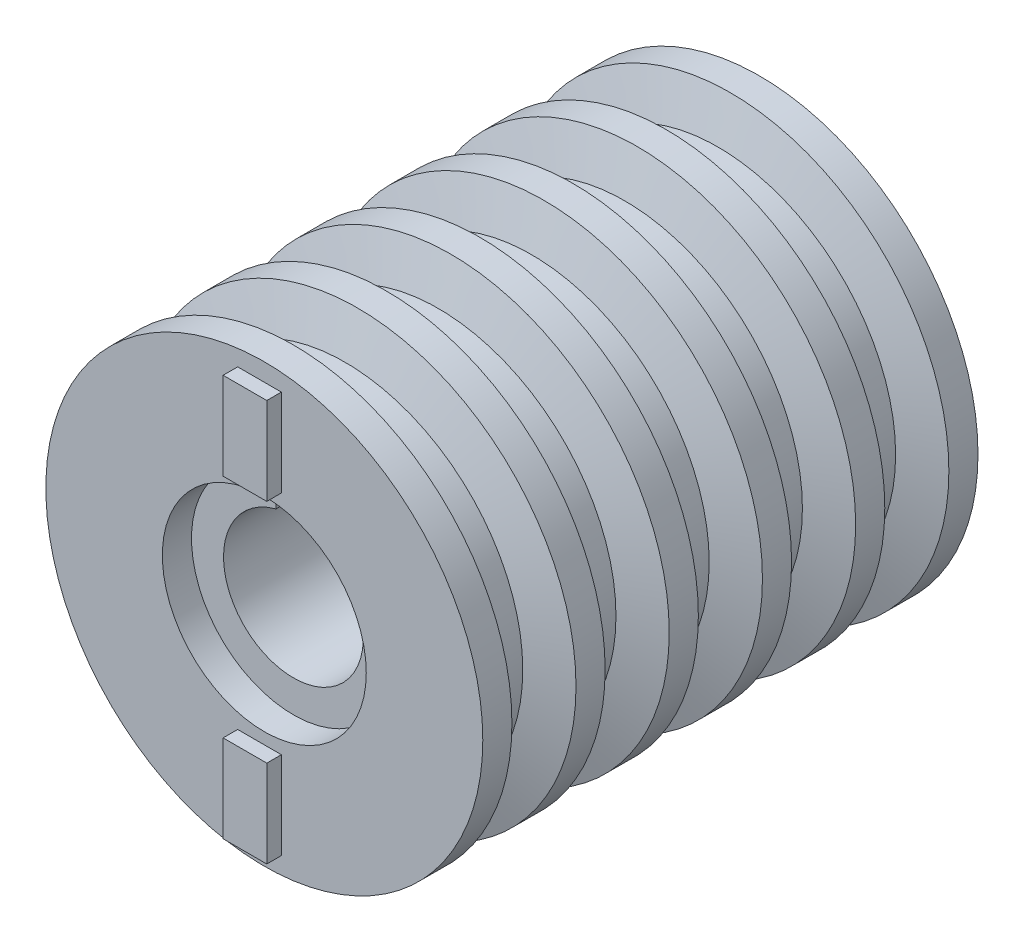
SolidWorks part; units mm, degrees
material "Gray Cast Iron"
ref_plane "Front Plane" through (0, 0, 0) normal (0, 0, 1) x (1, 0, 0)
ref_plane "Top Plane" through (0, 0, 0) normal (0, 1, 0) x (1, 0, 0)
ref_plane "Right Plane" through (0, 0, 0) normal (1, 0, 0) x (0, 0, -1)
sketch "Sketch1" plane through (0, 0, 0) normal (0, 0, 1) x (1, 0, 0)
  circle A0 centre (0, 0) radius 75
  circle A1 centre (0, 0) radius 24
  dimension "D1" = 48
  dimension "D2" = 150
extrude "Boss-Extrude1" add sketch "Sketch1" along normal mid plane 170
sketch "Sketch2" plane through (0, 0, 0) normal (0, 1, 0) x (1, 0, 0)
  line L0 (0, 0) -> (0, 105.7516) construction
  line L1 (75, 75) -> (61, 70.7198)
  line L2 (75, -85) -> (75, 85) construction
  line L3 (61, 70.7198) -> (61, 57.2802)
  line L4 (61, 57.2802) -> (75, 53)
  line L5 (75, 53) -> (75, 75)
  line L6 (75, 85) -> (-75, 85) construction
  line L7 (28.9279, 48) -> (103.4673, 48) construction
  line L8 (103.4673, 48) -> (103.4673, 16) construction
  line L9 (103.4673, 16) -> (25.53, 16) construction
  line L10 (25.53, 16) -> (25.53, -5.0684) construction
  line L11 (25.53, -5.0684) -> (102.8476, -5.0684) construction
  line L12 (102.8476, -5.0684) -> (102.8476, -48) construction
  line L13 (102.8476, -48) -> (25.53, -48) construction
  line L14 (75, 43) -> (75, 21)
  line L15 (61, 38.7198) -> (75, 43)
  line L16 (61, 25.2802) -> (61, 38.7198)
  line L17 (75, 21) -> (61, 25.2802)
  line L18 (75, -21) -> (75, -43)
  line L19 (61, -25.2802) -> (75, -21)
  line L20 (61, -38.7198) -> (61, -25.2802)
  line L21 (75, -43) -> (61, -38.7198)
  line L22 (75, 11) -> (61, 6.7198)
  line L23 (61, 6.7198) -> (61, -6.7198)
  line L24 (61, -6.7198) -> (75, -11)
  line L25 (75, -11) -> (75, 11)
  line L26 (75, -75) -> (75, -53)
  line L27 (61, -70.7198) -> (75, -75)
  line L28 (75, -53) -> (61, -57.2802)
  line L29 (61, -57.2802) -> (61, -70.7198)
  dimension "D1" = 10
  dimension "D2" = 22
  dimension "D3" = 73
  dimension "D4" = 73
  dimension "D5" = 14
  dimension "D6" = 5
  dimension "D7" = 5
  dimension "D8" = 5
revolve "Cut-Revolve1" cut sketch "Sketch2" angle 360 about L0
sketch "Sketch3" plane through (0, 0, 85) normal (0, 0, 1) x (1, 0, 0)
  line L1 (-6, 21) -> (6, 21)
  line L2 (-6, 21) -> (-6, 27)
  line L3 (-6, 27) -> (6, 27)
  line L4 (6, 21) -> (6, 27)
  line L5 (-6, 21) -> (6, 27) construction
  line L6 (-6, 27) -> (6, 21) construction
  circle A0 centre (0, 0) radius 24 construction
  point P0 (0, 24)
  dimension "D1" = 12
  dimension "D2" = 6
extrude "Cut-Extrude1" cut sketch "Sketch3" against normal through all
sketch "Sketch4" plane through (0, 0, 85) normal (0, 0, 1) x (1, 0, 0)
  circle A0 centre (0, 0) radius 35
  circle A1 centre (0, 0) radius 20
  dimension "D1" = 70
extrude "Cut-Extrude2" cut sketch "Sketch4" against normal blind 10
mirror "Mirror1" about plane through (0, 0, 0) normal (0, 0, 1) of "Cut-Extrude2"
sketch "Sketch5" plane through (0, 0, 85) normal (0, 0, 1) x (1, 0, 0)
  line L0 (0, 0) -> (99.8338, 0) construction
  line L1 (-9.1495, 68.9006) -> (5.8505, 68.9006)
  line L2 (-9.1495, 68.9006) -> (-9.1495, 38.9006)
  line L3 (-9.1495, 38.9006) -> (5.8505, 38.9006)
  line L4 (5.8505, 68.9006) -> (5.8505, 38.9006)
  line L11 (5.8505, -68.9006) -> (5.8505, -38.9006)
  line L12 (-9.1495, -38.9006) -> (5.8505, -38.9006)
  line L13 (-9.1495, -68.9006) -> (-9.1495, -38.9006)
  line L14 (-9.1495, -68.9006) -> (5.8505, -68.9006)
  point P15 (-7.8609, 34.1058)
  dimension "D1" = 15
  dimension "D2" = 30
extrude "Boss-Extrude2" add sketch "Sketch5" along normal blind 5
